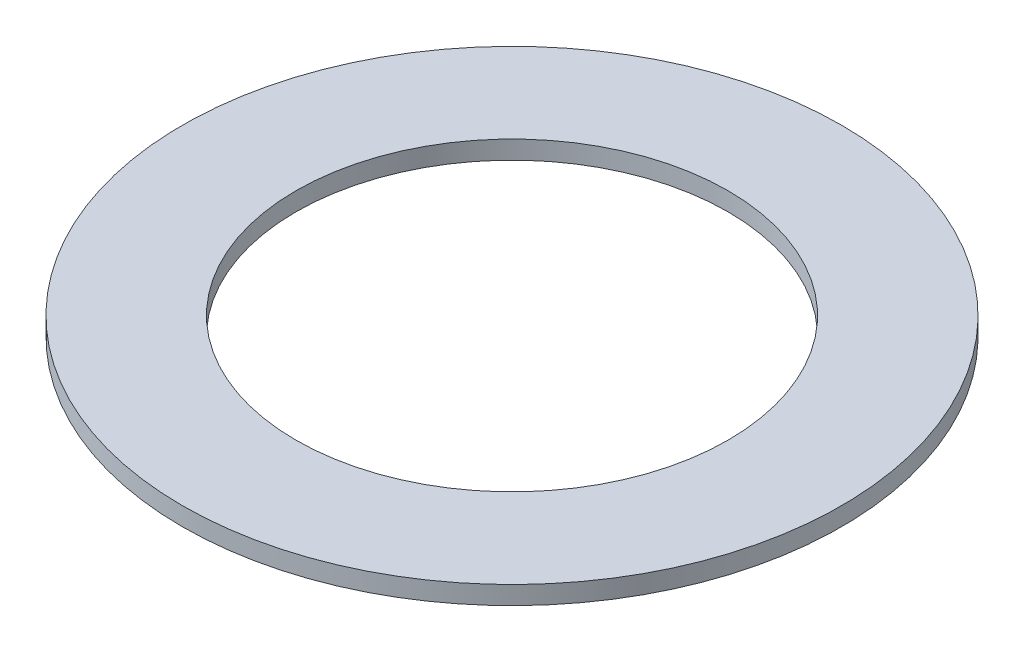
SolidWorks part; units mm, degrees
material "Delrin 2700 NC010, Low Viscosity Acetal Copolymer (SS)"
ref_plane "Front Plane" through (0, 0, 0) normal (0, 0, 1) x (1, 0, 0)
ref_plane "Top Plane" through (0, 0, 0) normal (0, 1, 0) x (1, 0, 0)
ref_plane "Right Plane" through (0, 0, 0) normal (1, 0, 0) x (0, 0, -1)
sketch "Sketch1" plane through (0, 0, 0) normal (0, 1, 0) x (1, 0, 0)
  circle A0 centre (0, 0) radius 5.9
  circle A1 centre (0, 0) radius 9
  dimension "D1" = 11.8
  dimension "D2" = 18
extrude "Boss-Extrude1" add sketch "Sketch1" along normal blind 0.5
